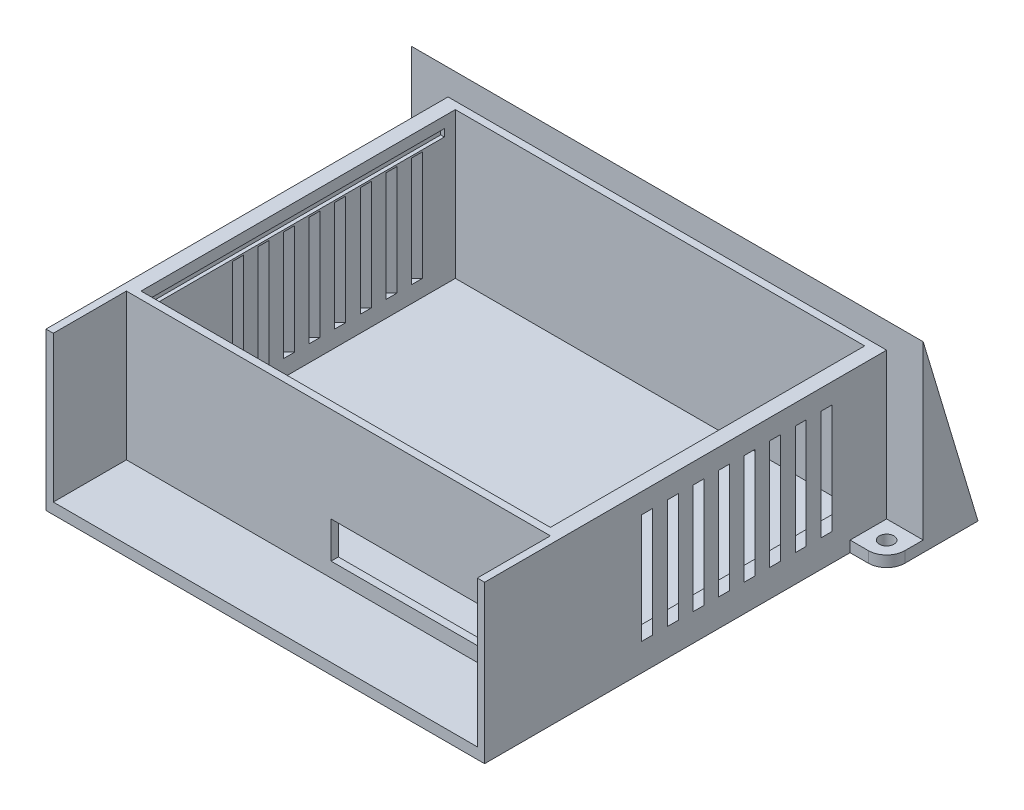
SolidWorks part; units mm, degrees
ref_plane "Front Plane" through (0, 0, 0) normal (0, 0, 1) x (1, 0, 0)
ref_plane "Top Plane" through (0, 0, 0) normal (0, 1, 0) x (1, 0, 0)
ref_plane "Right Plane" through (0, 0, 0) normal (1, 0, 0) x (0, 0, -1)
sketch "Sketch1" plane through (0, 0, 0) normal (0, 1, 0) x (1, 0, 0)
  line L1 (-37.8387, 67.957) -> (82.1613, 67.957)
  line L2 (-37.8387, 67.957) -> (-37.8387, -42.043)
  line L3 (-37.8387, -42.043) -> (82.1613, -42.043)
  line L4 (82.1613, 67.957) -> (82.1613, -42.043)
  dimension "D1" = 120
  dimension "D2" = 110
extrude "Boss-Extrude1" add sketch "Sketch1" along normal blind 3
sketch "Sketch2" plane through (0, 3, 0) normal (0, 1, 0) x (1, 0, 0)
  line L0 (-37.8387, 67.957) -> (-37.8387, -42.043)
  line L1 (-37.8387, -42.043) -> (-35.8387, -42.043)
  line L2 (-37.8387, -42.043) -> (82.1613, -42.043) construction
  line L3 (-35.8387, -42.043) -> (-35.8387, -22.043)
  line L4 (-35.8387, -22.043) -> (80.1613, -22.043)
  line L5 (80.1613, -22.043) -> (80.1613, -42.043)
  line L6 (80.1613, -42.043) -> (82.1613, -42.043)
  line L7 (82.1613, -42.043) -> (82.1613, 67.957)
  line L8 (82.1613, 67.957) -> (-37.8387, 67.957)
  line L10 (-33.8387, 65.957) -> (78.1613, 65.957)
  line L11 (-33.8387, 65.957) -> (-33.8387, -20.043)
  line L12 (-33.8387, -20.043) -> (78.1613, -20.043)
  line L13 (78.1613, 65.957) -> (78.1613, -20.043)
  dimension "D1" = 2
  dimension "D2" = 4
  dimension "D3" = 4
  dimension "D4" = 2
  dimension "D5" = 2
  dimension "D6" = 2
  dimension "D7" = 20
extrude "Boss-Extrude2" add sketch "Sketch2" along normal blind 40
sketch "Sketch3" plane through (82.1613, 0, 0) normal (1, 0, 0) x (0, 0, -1)
  line L0 (67.957, 50) -> (82.957, 0)
  line L1 (82.957, 0) -> (67.957, 0)
  line L2 (67.957, 0) -> (67.957, 50)
  dimension "D1" = 15
  dimension "D2" = 50
extrude "Boss-Extrude3" add sketch "Sketch3" along normal blind 10 and the other way blind 130
sketch "Skizze2" plane through (0, 0, 0) normal (0, -1, 0) x (1, 0, 0)
  line L1 (82.1613, -67.957) -> (92.1613, -67.957)
  line L2 (82.1613, -67.957) -> (82.1613, -57.957)
  line L3 (82.1613, -57.957) -> (87.1613, -57.957)
  line L4 (92.1613, -67.957) -> (92.1613, -62.957)
  line L5 (-37.8387, -67.957) -> (-47.8387, -67.957)
  line L6 (-37.8387, -67.957) -> (-37.8387, -57.957)
  line L7 (-37.8387, -57.957) -> (-42.8387, -57.957)
  line L8 (-47.8387, -67.957) -> (-47.8387, -62.957)
  arc A0 (87.1613, -57.957) -> (92.1613, -62.957) centre (87.1613, -62.957) cw
  arc A1 (-47.8387, -62.957) -> (-42.8387, -57.957) centre (-42.8387, -62.957) cw
  circle A2 centre (87.1613, -62.957) radius 2
  circle A3 centre (-42.8387, -62.957) radius 2
  dimension "D1" = 5
  dimension "D2" = 5
  dimension "D7" = 4
  dimension "D8" = 4
  dimension "D3" = 10
  dimension "D4" = 10
  dimension "D5" = 10
  dimension "D6" = 10
extrude "Aufsatz-Linear austragen1" add sketch "Skizze2" against normal blind 3
sketch "Skizze3" plane through (82.1613, 0, 0) normal (1, 0, 0) x (0, 0, -1)
  line L0 (-42.043, 0) -> (57.957, 0) construction
  line L1 (52.957, 37.5) -> (49.957, 37.5)
  line L2 (52.957, 37.5) -> (52.957, 7.5)
  line L3 (52.957, 7.5) -> (49.957, 7.5)
  line L4 (49.957, 37.5) -> (49.957, 7.5)
  line L5 (67.957, 50) -> (67.957, 3) construction
  line L6 (42.957, 37.5) -> (42.957, 7.5)
  line L7 (45.957, 7.5) -> (42.957, 7.5)
  line L8 (45.957, 37.5) -> (45.957, 7.5)
  line L9 (45.957, 37.5) -> (42.957, 37.5)
  line L10 (35.957, 37.5) -> (35.957, 7.5)
  line L11 (38.957, 7.5) -> (35.957, 7.5)
  line L12 (38.957, 37.5) -> (38.957, 7.5)
  line L13 (38.957, 37.5) -> (35.957, 37.5)
  line L14 (28.957, 37.5) -> (28.957, 7.5)
  line L15 (31.957, 7.5) -> (28.957, 7.5)
  line L16 (31.957, 37.5) -> (31.957, 7.5)
  line L17 (31.957, 37.5) -> (28.957, 37.5)
  line L18 (21.957, 37.5) -> (21.957, 7.5)
  line L19 (24.957, 7.5) -> (21.957, 7.5)
  line L20 (24.957, 37.5) -> (24.957, 7.5)
  line L21 (24.957, 37.5) -> (21.957, 37.5)
  line L22 (14.957, 37.5) -> (14.957, 7.5)
  line L23 (17.957, 7.5) -> (14.957, 7.5)
  line L24 (17.957, 37.5) -> (17.957, 7.5)
  line L25 (17.957, 37.5) -> (14.957, 37.5)
  line L26 (7.957, 37.5) -> (7.957, 7.5)
  line L27 (10.957, 7.5) -> (7.957, 7.5)
  line L28 (10.957, 37.5) -> (10.957, 7.5)
  line L29 (10.957, 37.5) -> (7.957, 37.5)
  line L30 (0.957, 37.5) -> (0.957, 7.5)
  line L31 (3.957, 7.5) -> (0.957, 7.5)
  line L32 (3.957, 37.5) -> (3.957, 7.5)
  line L33 (3.957, 37.5) -> (0.957, 37.5)
  line L34 (65.957, 3) -> (-20.043, 3) construction
  dimension "D1" = 30
  dimension "D2" = 3
  dimension "D3" = 7.5
  dimension "D4" = 15
  dimension "D5" = 8
sketch "Skizze4" plane through (0, 43, 0) normal (0, 1, 0) x (1, 0, 0)
  line L0 (82.1613, 51.5472) -> (78.1613, 55.5472) construction
  line L1 (82.1613, -42.043) -> (82.1613, 67.957) construction
  line L2 (78.1613, -20.043) -> (78.1613, 65.957) construction
extrude "Schnitt-Linear austragen1" cut sketch "Skizze3" along direction (-0.7071, 0, -0.7071) on the side against the normal blind 13
sketch "Skizze7" plane through (0, 43, 0) normal (0, 1, 0) x (1, 0, 0)
  line L0 (-37.8387, 55.0086) -> (-33.8387, 59.0086) construction
  line L1 (-37.8387, 67.957) -> (-37.8387, -42.043) construction
  line L2 (-33.8387, 65.957) -> (-33.8387, -20.043) construction
sketch "Skizze8" plane through (-37.8387, 0, 0) normal (-1, 0, 0) x (0, 0, 1)
  line L0 (-57.957, 0) -> (42.043, 0) construction
  line L1 (-52.957, 7.5) -> (-49.957, 7.5)
  line L2 (-52.957, 7.5) -> (-52.957, 37.5)
  line L3 (-52.957, 37.5) -> (-49.957, 37.5)
  line L4 (-49.957, 7.5) -> (-49.957, 37.5)
  line L5 (-67.957, 43) -> (-67.957, 3) construction
  line L6 (-45.957, 7.5) -> (-42.957, 7.5)
  line L7 (-45.957, 7.5) -> (-45.957, 37.5)
  line L8 (-45.957, 37.5) -> (-42.957, 37.5)
  line L9 (-42.957, 7.5) -> (-42.957, 37.5)
  line L10 (-38.957, 7.5) -> (-35.957, 7.5)
  line L11 (-38.957, 7.5) -> (-38.957, 37.5)
  line L12 (-38.957, 37.5) -> (-35.957, 37.5)
  line L13 (-35.957, 7.5) -> (-35.957, 37.5)
  line L14 (-31.957, 7.5) -> (-28.957, 7.5)
  line L15 (-31.957, 7.5) -> (-31.957, 37.5)
  line L16 (-31.957, 37.5) -> (-28.957, 37.5)
  line L17 (-28.957, 7.5) -> (-28.957, 37.5)
  line L18 (-24.957, 7.5) -> (-21.957, 7.5)
  line L19 (-24.957, 7.5) -> (-24.957, 37.5)
  line L20 (-24.957, 37.5) -> (-21.957, 37.5)
  line L21 (-21.957, 7.5) -> (-21.957, 37.5)
  line L22 (-17.957, 7.5) -> (-14.957, 7.5)
  line L23 (-17.957, 7.5) -> (-17.957, 37.5)
  line L24 (-17.957, 37.5) -> (-14.957, 37.5)
  line L25 (-14.957, 7.5) -> (-14.957, 37.5)
  line L26 (-10.957, 7.5) -> (-7.957, 7.5)
  line L27 (-10.957, 7.5) -> (-10.957, 37.5)
  line L28 (-10.957, 37.5) -> (-7.957, 37.5)
  line L29 (-7.957, 7.5) -> (-7.957, 37.5)
  line L30 (-3.957, 7.5) -> (-0.957, 7.5)
  line L31 (-3.957, 7.5) -> (-3.957, 37.5)
  line L32 (-3.957, 37.5) -> (-0.957, 37.5)
  line L33 (-0.957, 7.5) -> (-0.957, 37.5)
  dimension "D1" = 30
  dimension "D2" = 7.5
  dimension "D3" = 3
  dimension "D4" = 15
  dimension "D5" = 8
extrude "Schnitt-Linear austragen2" cut sketch "Skizze8" along direction (0.7071, 0, -0.7071) on the side against the normal blind 13
sketch "Skizze10" plane through (-33.8387, 0, 0) normal (1, 0, 0) x (0, 0, -1)
  line L0 (65.957, 43) -> (-20.043, 43) construction
  line L1 (62.957, 40) -> (-17.043, 40)
  line L2 (62.957, 40) -> (62.957, 38)
  line L3 (62.957, 38) -> (-17.043, 38)
  line L4 (-17.043, 40) -> (-17.043, 38)
  line L5 (-20.043, 43) -> (-20.043, 3) construction
  dimension "D1" = 3
  dimension "D2" = 2
  dimension "D3" = 80
  dimension "D4" = 3
sketch "Skizze11" plane through (78.1613, 0, 0) normal (-1, 0, 0) x (0, 0, 1)
  line L0 (20.043, 43) -> (-65.957, 43) construction
  line L1 (-62.957, 38) -> (17.043, 38)
  line L2 (-62.957, 38) -> (-62.957, 40)
  line L3 (-62.957, 40) -> (17.043, 40)
  line L4 (17.043, 38) -> (17.043, 40)
  line L5 (20.043, 43) -> (20.043, 3) construction
  point P6 (17.043, 39)
  dimension "D1" = 2
  dimension "D2" = 80
  dimension "D3" = 3
  dimension "D4" = 3
extrude "Schnitt-Linear austragen3" cut sketch "Skizze10" against normal blind 1
extrude "Schnitt-Linear austragen4" cut sketch "Skizze11" against normal blind 1
sketch "Skizze12" plane through (0, 0, 22.043) normal (0, 0, 1) x (1, 0, 0)
  line L0 (80.1613, 43) -> (80.1613, 3) construction
  line L1 (75.1613, 17) -> (20.1613, 17)
  line L2 (75.1613, 17) -> (75.1613, 7)
  line L3 (75.1613, 7) -> (20.1613, 7)
  line L4 (20.1613, 17) -> (20.1613, 7)
  line L5 (-35.8387, 3) -> (80.1613, 3) construction
  dimension "D1" = 10
  dimension "D2" = 55
  dimension "D3" = 5
  dimension "D4" = 4
extrude "Schnitt-Linear austragen5" cut sketch "Skizze12" against normal blind 31
